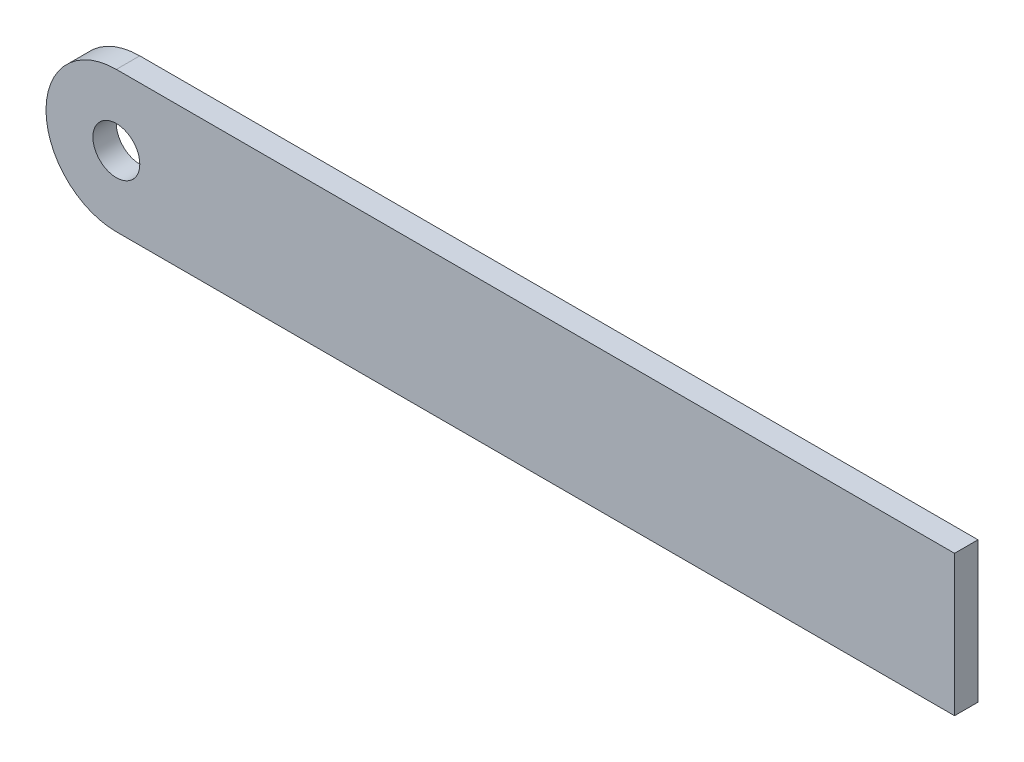
SolidWorks part; units mm, degrees
material "1023 Tôle d'acier au carbone (SS)"
ref_plane "Plan de face" through (0, 0, 0) normal (0, 0, 1) x (1, 0, 0)
ref_plane "Plan de dessus" through (0, 0, 0) normal (0, 1, 0) x (1, 0, 0)
ref_plane "Plan de droite" through (0, 0, 0) normal (1, 0, 0) x (0, 0, -1)
sketch "Esquisse1" plane through (0, 0, 0) normal (0, 0, 1) x (1, 0, 0)
  line L0 (-71.5, 0) -> (71.5, 0) construction
  line L1 (-71.5, 6) -> (71.5, 6)
  line L2 (-71.5, -6) -> (71.5, -6)
  arc A0 (-71.5, 6) -> (-71.5, -6) centre (-71.5, 0) ccw
  arc A1 (71.5, -6) -> (71.5, 6) centre (71.5, 0) ccw
  circle A2 centre (-71.5, 0) radius 2
  circle A3 centre (71.5, 0) radius 2
  point P2 (0, 0)
  dimension "D3" = 4
  dimension "D4" = 4
  dimension "D1" = 143
  dimension "D2" = 6
extrude "Boss.-Extru.1" add sketch "Esquisse1" along normal blind 2 contours L1 A1 L2 A0
sketch "Esquisse3" plane through (0, 0, 2) normal (0, 0, 1) x (1, 0, 0)
  line L0 (0, 0) -> (0, 10.9627)
  line L1 (0, 10.9627) -> (80.2343, 10.9627)
  line L2 (80.2343, 10.9627) -> (80.2343, -13.9814)
  line L3 (80.2343, -13.9814) -> (0, -13.9814)
  line L4 (0, -13.9814) -> (0, 0)
extrude "Enlèv. mat.-Extru.1" cut sketch "Esquisse3" against normal through all and the other way through all
